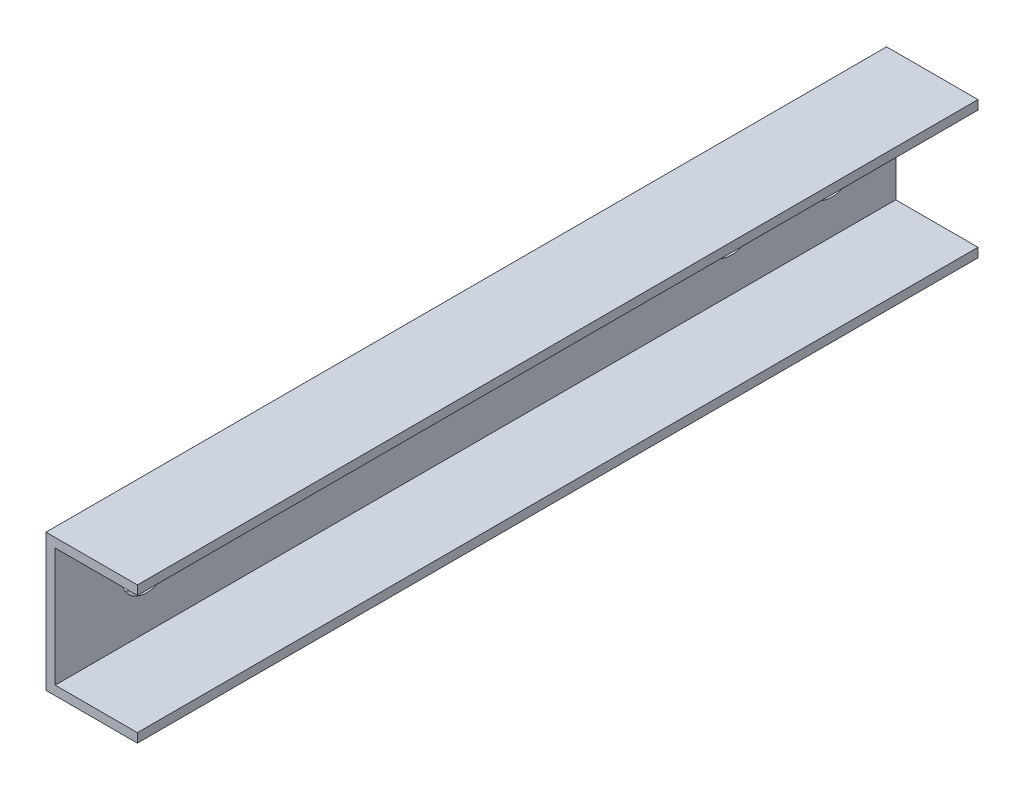
SolidWorks part; units mm, degrees
ref_plane "Alzado" through (0, 0, 0) normal (1, 0, 0) x (0, 1, 0)
ref_plane "Planta" through (0, 0, 0) normal (0, 0, 1) x (0, 1, 0)
ref_plane "Vista lateral" through (0, 0, 0) normal (0, 1, 0) x (-1, 0, 0)
sketch "Croquis1" plane through (0, 0, 0) normal (1, 0, 0) x (0, 1, 0)
  line L1 (0, 0) -> (13, 0)
  line L2 (0, 0) -> (0, 90)
  line L3 (0, 90) -> (13, 90)
  line L4 (13, 0) -> (13, 90)
  dimension "D1" = 13
  dimension "D2" = 90
extrude "Extruir-Lámina1" add sketch "Croquis1" along normal blind 10 thin
sketch "Croquis2" plane through (0, 0, -1) normal (0, 0, -1) x (1, 0, 0)
  line L0 (0, 0) -> (0, -13) construction
  line L1 (0, 0) -> (0, -13)
  line L2 (0, -13) -> (10, -13)
  line L3 (0, 0) -> (10, 0)
  line L4 (0, 1) -> (0, -14)
  line L5 (0, -14) -> (10, -14)
  line L6 (10, -14) -> (10, 1)
  line L7 (10, 1) -> (0, 1)
  line L8 (0, 1) -> (0, -14)
  line L9 (0, -14) -> (10, -14)
  line L10 (10, -14) -> (10, 1)
  line L11 (10, 1) -> (0, 1)
  line L12 (0, 0) -> (0, -13)
  line L13 (10, 0) -> (10, -13) construction
  line L14 (10, 0) -> (10, -13)
  line L15 (1, 0) -> (1, -13)
  line M5 (0, 1) -> (0, -14)
  line M7 (10, -14) -> (10, 1)
  dimension "D2" = 1
  dimension "D1" = 0
extrude "Cortar-Extruir2" cut sketch "Croquis2" against normal through all contours L3 L2 M5 M7
sketch "Croquis5" plane through (0, 0, 0) normal (-1, 0, 0) x (0, -1, 0)
  line L1 (-13, 90) -> (0, 90)
  line L2 (-13, 90) -> (-13, 0)
  line L3 (-13, 0) -> (0, 0)
  line L4 (0, 90) -> (0, 0)
extrude "Saliente-Extruir1" add sketch "Croquis5" against normal up to surface (1 mm away) up to face at (1, 6.5, 90.5)
sketch "Croquis6" plane through (1, 0, 0) normal (1, 0, 0) x (0, 1, 0)
  line L0 (6.5, 91) -> (6.5, -1) construction
  line L1 (-9.7413, 81) -> (21.8326, 81) construction
  line L2 (-8.1873, 6) -> (21.8326, 6) construction
  line L4 (13, -1) -> (13, 91)
  line L5 (13, 91) -> (0, 91)
  line L6 (0, 91) -> (0, -1)
  line L7 (0, -1) -> (13, -1)
  line L8 (13, -1) -> (13, 91)
  line L9 (13, 91) -> (0, 91)
  line L10 (0, 91) -> (0, -1)
  line L11 (0, -1) -> (13, -1)
  circle A0 centre (6.5, 6) radius 2.75
  circle A1 centre (6.5, 81) radius 2.75
  circle A2 centre (6.5, 17) radius 2.75
  dimension "D4" = 5.5
  dimension "D2" = 10
  dimension "D3" = 75
  dimension "D5" = 11
  dimension "D1" = 0
extrude "Cortar-Extruir3" cut sketch "Croquis6" against normal through all both and the other way through all contours A2 | A1 | A0
